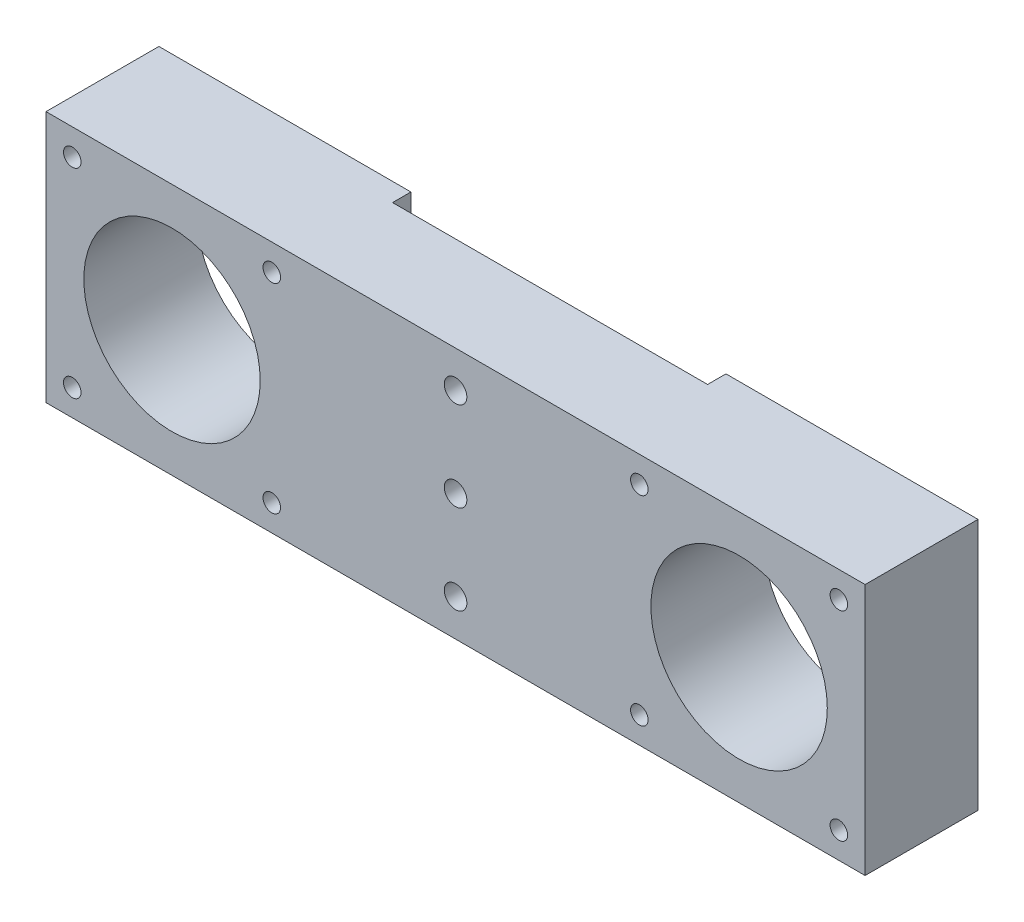
SolidWorks part; units mm, degrees
material "打印件"
ref_plane "前视基准面" through (0, 0, 0) normal (0, 0, 1) x (1, 0, 0)
ref_plane "上视基准面" through (0, 0, 0) normal (0, 1, 0) x (1, 0, 0)
ref_plane "右视基准面" through (0, 0, 0) normal (1, 0, 0) x (0, 0, -1)
sketch "草图1" plane through (0, 0, 0) normal (0, 0, 1) x (1, 0, 0)
  line L1 (24, -24) -> (-24, -24)
  line L2 (24, -24) -> (24, 24)
  line L3 (24, 24) -> (-24, 24)
  line L4 (-24, -24) -> (-24, 24)
  line L5 (24, -24) -> (-24, 24) construction
  line L6 (24, 24) -> (-24, -24) construction
  line L7 (19, -19) -> (-19, -19) construction
  line L8 (19, -19) -> (19, 19) construction
  line L9 (19, 19) -> (-19, 19) construction
  line L10 (-19, -19) -> (-19, 19) construction
  line L11 (19, -19) -> (-19, 19) construction
  line L12 (19, 19) -> (-19, -19) construction
  circle A0 centre (0, 0) radius 16.8
  circle A1 centre (-19, 19) radius 1.67
  circle A2 centre (19, 19) radius 1.67
  circle A3 centre (19, -19) radius 1.67
  circle A4 centre (-19, -19) radius 1.67
  point P0 (0, 0)
  point P12 (0, 19)
  dimension "D3" = 33.6
  dimension "D6" = 3.34
  dimension "D1" = 48
  dimension "D2" = 48
  dimension "D4" = 5
  dimension "D5" = 5
extrude "凸台-拉伸1" add sketch "草图1" along normal blind 21.5
ref_plane "基准面1" through (0, 0, 21.5) normal (0, 0, 1) x (1, 0, 0)
sketch "草图3" plane through (0, 0, 21.5) normal (0, 0, 1) x (1, 0, 0)
  line L0 (24, -24) -> (84, -24)
  line L1 (84, -24) -> (84, 24)
  line L2 (84, 24) -> (24, 24)
  line L3 (24, -24) -> (24, 24) construction
  line L4 (24, 24) -> (24, -24)
  line L5 (54, 24) -> (54, -24) construction
  circle A0 centre (54, 17) radius 2.15
  circle A1 centre (54, 0) radius 2.15
  circle A2 centre (54, -17) radius 2.15
  dimension "D4" = 4.3
  dimension "D1" = 60
  dimension "D2" = 7
  dimension "D3" = 7
extrude "凸台-拉伸2" add sketch "草图3" against normal blind 18
pattern_linear "阵列(线性)2" count 2 spacing 108 along (1, 0, 0) of "凸台-拉伸1"
